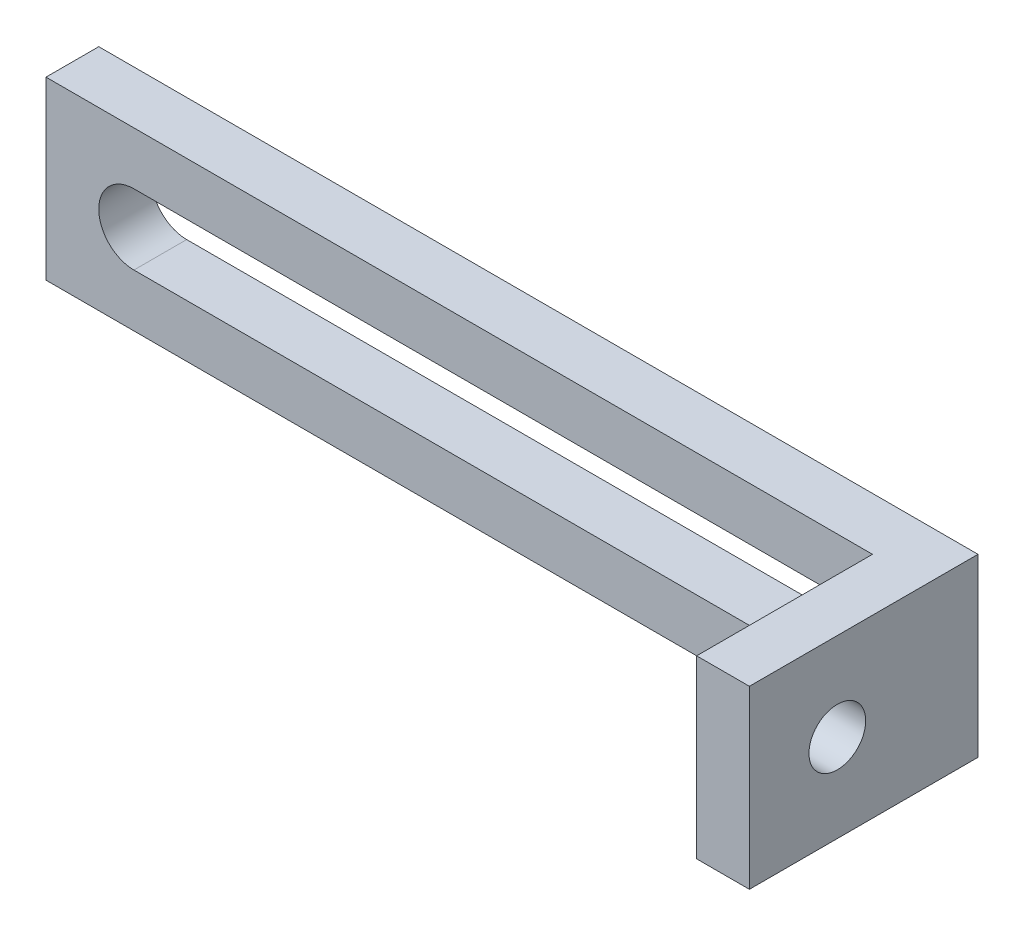
SolidWorks part; units mm, degrees
ref_plane "Front Plane" through (0, 0, 0) normal (0, 0, 1) x (1, 0, 0)
ref_plane "Top Plane" through (0, 0, 0) normal (0, 1, 0) x (1, 0, 0)
ref_plane "Right Plane" through (0, 0, 0) normal (1, 0, 0) x (0, 0, -1)
sketch "Sketch1" plane through (0, 0, 0) normal (0, 0, 1) x (1, 0, 0)
  line L1 (-25, 5) -> (25, 5)
  line L2 (-25, 5) -> (-25, -5)
  line L3 (-25, -5) -> (25, -5)
  line L4 (25, 5) -> (25, -5)
  line L5 (-25, 5) -> (25, -5) construction
  line L6 (-25, -5) -> (25, 5) construction
  point P0 (0, 0)
  dimension "D1" = 10
  dimension "D2" = 50
extrude "Boss-Extrude1" add sketch "Sketch1" along normal blind 3
sketch "Sketch2" plane through (0, 0, 3) normal (0, 0, 1) x (1, 0, 0)
  line L0 (-25, -5) -> (25, -5) construction
  line L1 (25, 5) -> (22, 5)
  line L2 (25, 5) -> (25, -5)
  line L3 (25, -5) -> (22, -5)
  line L4 (22, 5) -> (22, -5)
  dimension "D1" = 3
extrude "Boss-Extrude2" add sketch "Sketch2" along normal blind 10
sketch "Sketch3" plane through (25, 0, 0) normal (1, 0, 0) x (0, 0, -1)
  line L0 (-13, 5) -> (0, 5) construction
  line L1 (-13, 5) -> (-13, -5) construction
  circle A0 centre (-8, 0) radius 1.6144
  dimension "D1" = 5
  dimension "D2" = 5
extrude "Cut-Extrude1" cut sketch "Sketch3" against normal blind 10
sketch "Sketch5" plane through (0, 0, 0) normal (0, 0, -1) x (-1, 0, 0)
  line L0 (20, 0) -> (-20.3064, 0) construction
  line L1 (20, -2) -> (-20.3064, -2)
  line L2 (20, 2) -> (-20.3064, 2)
  line L3 (25, -5) -> (-25, -5) construction
  line L4 (25, 5) -> (25, -5) construction
  arc A0 (20, -2) -> (20, 2) centre (20, 0) ccw
  arc A1 (-20.3064, 2) -> (-20.3064, -2) centre (-20.3064, 0) ccw
  point P2 (-0.1532, 0)
  dimension "D1" = 2
  dimension "D3" = 5
  dimension "D2" = 5
extrude "Cut-Extrude2" cut sketch "Sketch5" against normal blind 10
